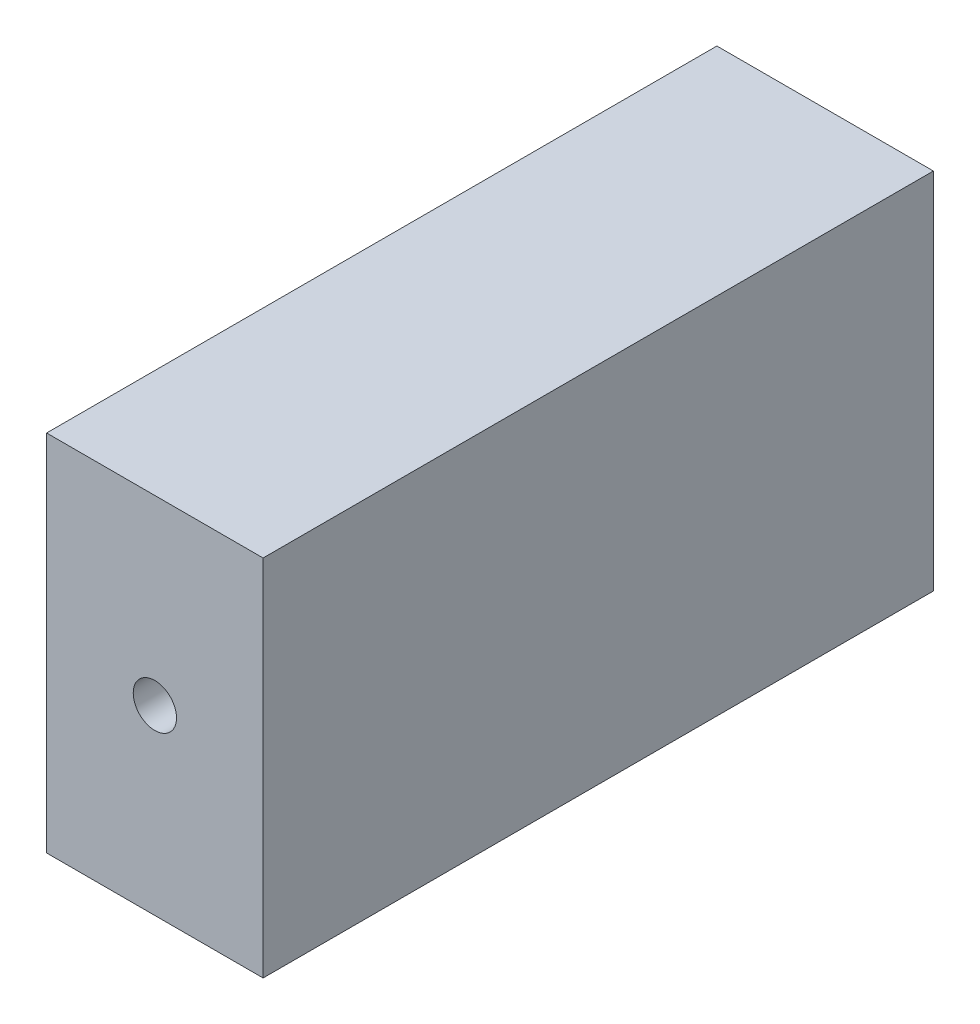
SolidWorks part; units mm, degrees
ref_plane "Front Plane" through (0, 0, 0) normal (0, 0, 1) x (1, 0, 0)
ref_plane "Top Plane" through (0, 0, 0) normal (0, 1, 0) x (1, 0, 0)
ref_plane "Right Plane" through (0, 0, 0) normal (1, 0, 0) x (0, 0, -1)
sketch "Sketch1" plane through (0, 0, 0) normal (1, 0, 0) x (0, 0, -1)
  line L1 (-78.6359, 42.6744) -> (78.6359, 42.6744)
  line L2 (-78.6359, 42.6744) -> (-78.6359, -42.6744)
  line L3 (-78.6359, -42.6744) -> (78.6359, -42.6744)
  line L4 (78.6359, 42.6744) -> (78.6359, -42.6744)
  line L5 (-78.6359, 42.6744) -> (78.6359, -42.6744) construction
  line L6 (-78.6359, -42.6744) -> (78.6359, 42.6744) construction
  point P0 (0, 0)
extrude "Boss-Extrude1" add sketch "Sketch1" along normal mid plane 50.8
sketch "Sketch11" plane through (0, 0, 0) normal (1, 0, 0) x (0, 0, -1)
  line L0 (-86.8859, 0) -> (-36.0139, 0)
  line L1 (-36.0139, 0) -> (-23.5066, 28.3729)
  line L2 (-23.5066, 28.3729) -> (26.4527, 28.3729)
  line L3 (26.4527, 28.3729) -> (46.2429, 0)
  line L4 (46.2429, 0) -> (78.8699, 0)
sweep "Cut-Sweep2" cut path "Sketch11" circular profile diameter 10.16 parameters "D3"=10.16
